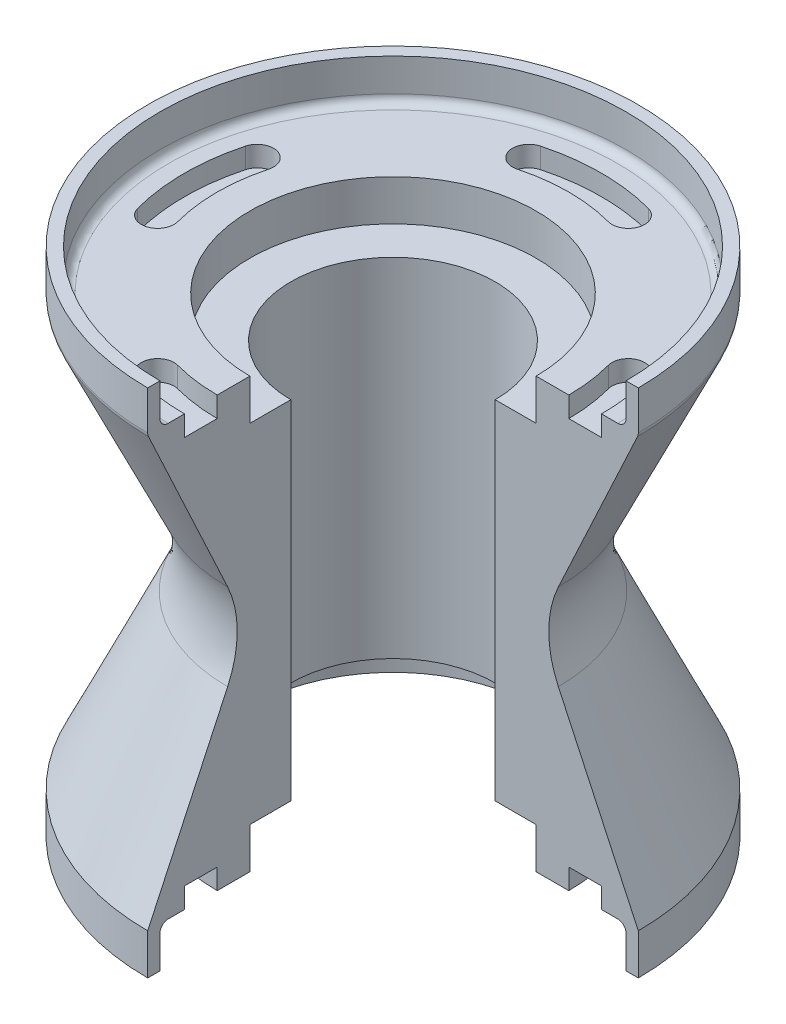
SolidWorks part; units mm, degrees
material "Plain Carbon Steel"
ref_plane "Front Plane" through (0, 0, 0) normal (0, 0, 1) x (1, 0, 0)
ref_plane "Top Plane" through (0, 0, 0) normal (0, 1, 0) x (1, 0, 0)
ref_plane "Right Plane" through (0, 0, 0) normal (1, 0, 0) x (0, 0, -1)
sketch "Sketch1" plane through (0, 0, 0) normal (0, 1, 0) x (1, 0, 0)
  circle A0 centre (0, 0) radius 60
  dimension "D1" = 120
extrude "Boss-Extrude1" add sketch "Sketch1" along normal blind 52.5 draft 25
mirror "Mirror1" [suppressed] about plane through (0, 0, 0) normal (0, 1, 0)
mirror "Mirror2" about plane through (0, 52.5, 0) normal (0, 1, 0) of "Boss-Extrude1"
sketch "Sketch2" plane through (0, 105, 0) normal (0, 1, 0) x (1, 0, 0)
  circle A3 centre (0, 0) radius 25
  dimension "D1" = 50
extrude "Cut-Extrude1" cut sketch "Sketch2" against normal through all both and the other way through all
sketch "Sketch3" plane through (0, 105, 0) normal (0, 1, 0) x (1, 0, 0)
  circle A0 centre (0, 0) radius 35
  dimension "D1" = 70
extrude "Cut-Extrude2" cut sketch "Sketch3" against normal blind 10
sketch "Sketch5" plane through (0, 0, 0) normal (0, -1, 0) x (1, 0, 0)
  circle A0 centre (0, 0) radius 35
  circle A2 centre (0, 0) radius 35 construction
extrude "Cut-Extrude5" cut sketch "Sketch5" against normal blind 10
fillet "Fillet1" radius 25 1 edges at (0, 52.5, 35.5188)
sketch "Sketch7" plane through (0, 105, 0) normal (0, 1, 0) x (1, 0, 0)
  line L0 (0, -60) -> (0, 0)
  line L1 (0, 0) -> (60, 0)
  circle A0 centre (0, 0) radius 60 construction
  arc A1 (0, -60) -> (60, 0) centre (0, 0) ccw
extrude "Cut-Extrude6" cut sketch "Sketch7" against normal through all both and the other way through all
sketch "Sketch8" plane through (0, 0, 0) normal (0, -1, 0) x (1, 0, 0)
  line L3 (0, 57) -> (0, 60)
  line L5 (60, 0) -> (57, 0)
  line L8 (60, -1) -> (35, -1)
  line L9 (60, -1) -> (59.9917, -1)
  arc A3 (0, 60) -> (60, 0) centre (0, 0) ccw construction
  arc A4 (0, 57) -> (57, 0) centre (0, 0) ccw
  arc A5 (0, 57) -> (57, 0) centre (0, 0) ccw
  arc A8 (0, 60) -> (60, 0) centre (0, 0) ccw
  point P3 (0, 59)
  point P5 (0, 0)
  point P7 (0.5889, 61.8559)
  dimension "D1" = 3
  dimension "D2" = 1
extrude "Boss-Extrude2" add sketch "Sketch8" along normal blind 10 contours A5 L5 A8 L3
ref_plane "Plane1" through (0, 52.5, 0) normal (0, 1, 0) x (1, 0, 0)
mirror "Mirror3" about plane through (0, 52.5, 0) normal (0, 1, 0) of "Boss-Extrude2"
sketch "Sketch9" plane through (0, 0, 0) normal (0, -1, 0) x (1, 0, 0)
  line L0 (0, 0) -> (-82.2177, 0) construction
  line L1 (0, 0) -> (-45.3985, -12.1645) construction
  circle A0 centre (0, 0) radius 47 construction
  arc A1 (-45.3985, 12.1645) -> (-45.3985, -12.1645) centre (0, 0) ccw construction
  arc A6 (-49.2622, 13.1998) -> (-49.2622, -13.1998) centre (0, 0) ccw
  arc A7 (-41.5348, 11.1292) -> (-41.5348, -11.1292) centre (0, 0) ccw
  arc A8 (-41.5348, 11.1292) -> (-49.2622, 13.1998) centre (-45.3985, 12.1645) ccw
  arc A9 (-49.2622, -13.1998) -> (-41.5348, -11.1292) centre (-45.3985, -12.1645) ccw
  arc A10 (11.1292, 41.5348) -> (-11.1292, 41.5348) centre (0, 0) ccw
  arc A11 (11.1292, 41.5348) -> (13.1998, 49.2622) centre (12.1645, 45.3985) ccw
  arc A12 (-13.1998, 49.2622) -> (-11.1292, 41.5348) centre (-12.1645, 45.3985) ccw
  arc A13 (13.1998, 49.2622) -> (-13.1998, 49.2622) centre (0, 0) ccw
  arc A14 (12.1645, 45.3985) -> (-12.1645, 45.3985) centre (0, 0) ccw construction
  arc A15 (41.5348, -11.1292) -> (41.5348, 11.1292) centre (0, 0) ccw
  arc A16 (41.5348, -11.1292) -> (49.2622, -13.1998) centre (45.3985, -12.1645) ccw
  arc A17 (49.2622, 13.1998) -> (41.5348, 11.1292) centre (45.3985, 12.1645) ccw
  arc A18 (49.2622, -13.1998) -> (49.2622, 13.1998) centre (0, 0) ccw
  arc A19 (45.3985, -12.1645) -> (45.3985, 12.1645) centre (0, 0) ccw construction
  arc A20 (-11.1292, -41.5348) -> (11.1292, -41.5348) centre (0, 0) ccw
  arc A21 (-11.1292, -41.5348) -> (-13.1998, -49.2622) centre (-12.1645, -45.3985) ccw
  arc A22 (13.1998, -49.2622) -> (11.1292, -41.5348) centre (12.1645, -45.3985) ccw
  arc A23 (-13.1998, -49.2622) -> (13.1998, -49.2622) centre (0, 0) ccw
  arc A24 (-12.1645, -45.3985) -> (12.1645, -45.3985) centre (0, 0) ccw construction
  point P5 (-47, 0)
  point P18 (0, 47)
  point P25 (47, 0)
  point P32 (0, -47)
  dimension "D1" = 94
  dimension "D2" = 4
  dimension "D3" = 15
  dimension "D4" = 4
extrude "Cut-Extrude7" cut sketch "Sketch9" against normal blind 5
mirror "Mirror4" about plane through (0, 52.5, 0) normal (0, 1, 0) of "Cut-Extrude7"
fillet "Fillet2" radius 2 2 edges at (-40.3051, 0, -40.3051)
fillet "Fillet3" radius 2 1 edges at (-40.3051, 105, -40.3051)
equation "\"A\" = 105"
equation "\"B\" = 120"
equation "\"C\"= 25"
equation "\"D3@Boss-Extrude1\"=\"C\""
equation "\"D1@Sketch1\"=\"B\""
equation "\"D1@Boss-Extrude1\"=\"A\"/2"
